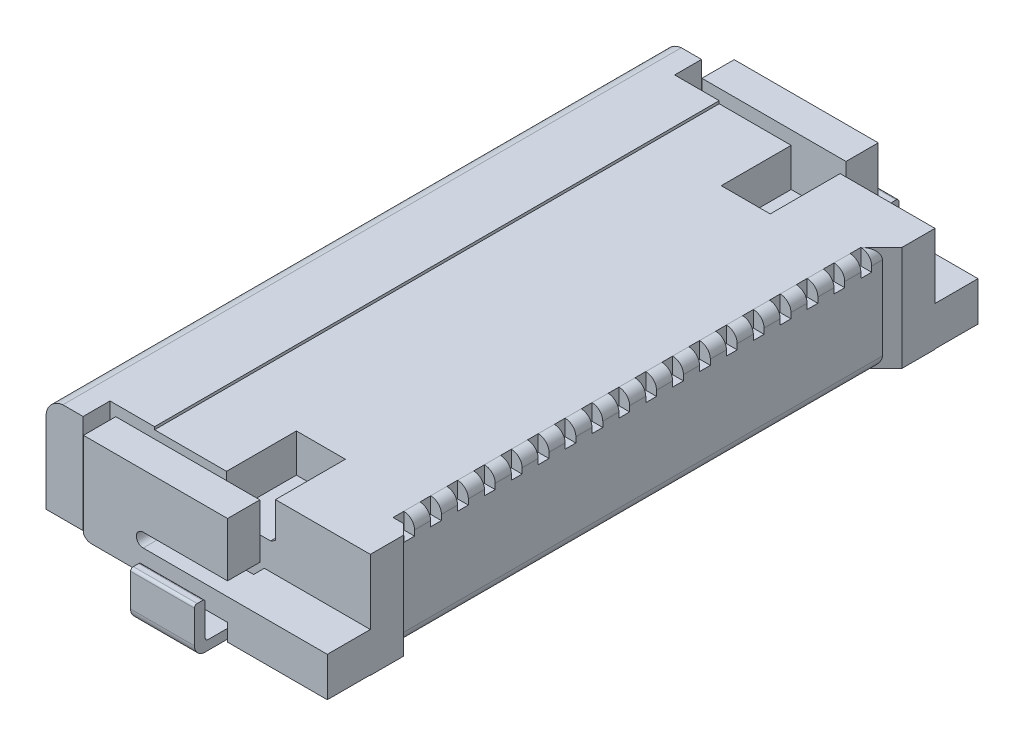
SolidWorks part; units mm, degrees
ref_plane "Front Plane" through (0, 0, 0) normal (0, 0, 1) x (1, 0, 0)
ref_plane "Top Plane" through (0, 0, 0) normal (0, 1, 0) x (1, 0, 0)
ref_plane "Right Plane" through (0, 0, 0) normal (1, 0, 0) x (0, 0, -1)
sketch "Sketch5" plane through (0, 0, 0) normal (0, 0, 1) x (1, 0, 0)
  line L0 (40.6667, 46) -> (203.3333, 46) construction
  line L1 (1.0365, 0.0671) -> (5.5705, 0.0671)
  line L2 (5.5705, 0.0671) -> (5.5705, 2.0592)
  line L3 (5.5705, 2.0592) -> (1.0365, 2.0592)
  line L4 (1.0365, 2.0592) -> (1.0365, 0.0671)
  line L5 (1.0365, 0.9096) -> (0.7294, 0.9096)
  line L6 (0.7294, 0.9096) -> (0.7294, 2.0592)
  line L7 (0.7294, 2.0592) -> (1.0365, 2.0592)
  line L8 (2.4126, 0.8573) -> (2.4126, 0.0671)
  line L9 (2.4126, 0.8573) -> (3.5997, 0.8573)
  line L10 (3.5997, 0.8573) -> (3.5997, 0.0671)
  line L11 (3.5997, 0.7994) -> (5.5705, 0.7994)
  line L12 (2.4126, 0.7994) -> (2.1463, 0.7994)
  line L13 (2.1463, 1.0542) -> (3.7156, 1.0542)
  line L14 (3.7156, 1.0542) -> (3.7156, 2.0592)
  line L15 (2.4126, 0.175) -> (1.0365, 0.175)
  line L16 (3.5997, 0.175) -> (5.5705, 0.175)
  line L17 (2.4126, 0.3858) -> (1.1847, 0.3858)
  line L18 (0.0415, 1.6702) -> (0.0415, 0.2199)
  line L19 (0.0415, 0.2199) -> (0.7294, 0.2199)
  line L20 (0.7294, 0.2199) -> (0.7294, 0.9096)
  line L21 (0.7294, 2.0592) -> (0.3527, 2.0592)
  line L22 (3.8064, 2.0592) -> (3.8064, 1.3482)
  line L23 (3.8064, 1.3482) -> (3.7156, 1.2979)
  line L24 (0.9408, 0.9096) -> (0.9408, 1.2134)
  line L25 (0.9408, 1.2134) -> (1.0365, 1.2134)
  line L26 (3.5997, 0.3858) -> (3.7156, 0.3858)
  line L27 (3.7156, 0.3858) -> (3.7156, 0.175)
  arc A0 (2.1463, 0.7994) -> (2.1463, 1.0542) centre (2.1463, 0.9268) cw
  arc A1 (0.0415, 1.6702) -> (0.3527, 2.0592) centre (0.3916, 1.7091) cw
  spline S0 degree 2 poles (1.1847, 0.3858) (1.082, 0.3886) (1.0365, 0.477) knots 0 0 0 1 1 1
extrude "Boss-Extrude1" add sketch "Sketch5" against normal blind 0.6 contours S0 L17 L8 L12 A0 L13 L14 L3 L4
sketch "Sketch7" plane through (0, 0, 0) normal (0, 0, 1) x (1, 0, 0)
  line L0 (5.5705, 0.0671) -> (5.5705, 2.0592) construction
  line L2 (3.7156, 0.3858) -> (3.7156, 0.175) construction
  line L3 (3.5997, 0.3858) -> (3.7156, 0.3858) construction
  line L4 (3.5997, 0.7994) -> (5.5705, 0.7994) construction
  line L10 (5.5705, 0.175) -> (5.5705, 0.7994)
  line L11 (3.7156, 0.175) -> (3.7156, 0.0671)
  line L12 (3.7156, 0.3858) -> (3.7156, 0.175)
  line L13 (3.5997, 0.3858) -> (3.7156, 0.3858)
  line L14 (3.5997, 0.7994) -> (5.5705, 0.7994)
  line L15 (3.5997, 0.7994) -> (3.5997, 0.3858)
  line L16 (1.0365, 0.0671) -> (5.5705, 0.0671) construction
  line L17 (3.7156, 0.0671) -> (5.5705, 0.0671)
  line L18 (5.5705, 0.0671) -> (5.5705, 0.175)
  line L20 (2.4126, 0.3858) -> (3.5997, 0.3858)
  line L21 (2.4126, 0.7994) -> (3.5997, 0.7994)
  line L24 (2.4126, 0.7994) -> (2.4126, 0.3858)
extrude "Boss-Extrude2" add sketch "Sketch7" against normal blind 0.8 separate body contours L17 L18 L10 L14 L15 L13 L12 L11
sketch "Sketch8" plane through (0, 0, 0) normal (0, 0, 1) x (1, 0, 0)
  line L0 (3.5997, 0.7994) -> (2.4126, 0.7994)
  line L1 (3.5997, 0.3858) -> (2.4126, 0.3858)
  line L2 (3.5997, 0.8573) -> (3.5997, 0.0671) construction
  line L3 (2.4126, 0.8573) -> (2.4126, 0.0671) construction
  line L4 (3.5997, 0.7994) -> (3.5997, 0.3858)
  line L5 (2.4126, 0.7994) -> (2.4126, 0.3858)
extrude "Boss-Extrude3" add sketch "Sketch8" against normal blind 0.6
sketch "Sketch11" plane through (0, 0, 0) normal (0, 1, 0) x (1, 0, 0)
  line L0 (5.5705, 0.8) -> (5.5705, 1.4131)
  line L1 (5.5705, 1.4131) -> (5.3077, 1.5403)
  line L2 (5.3077, 1.5403) -> (5.3077, 9.05)
  line L3 (3.5997, 0) -> (5.5705, 0) construction
  line L4 (5.3077, 9.05) -> (1.7077, 9.05)
  line L5 (1.7077, 9.05) -> (1.7077, 0.8)
  line L6 (1.7077, 0.8) -> (5.5705, 0.8)
  dimension "D1" = 9.05
  dimension "D2" = 3.6
ref_plane "Plane1" through (0, 0.06, 0) normal (0, 1, 0) x (1, 0, 0)
sketch "Sketch13" plane through (0, 0.06, 0) normal (0, 1, 0) x (1, 0, 0)
  line L0 (3.7156, 0) -> (1.0365, 0) construction
  line L2 (5.5705, 0.8) -> (5.5705, 1.4131) construction
  line L6 (5.3077, 6.05) -> (1.6924, 6.05)
  line L7 (5.5705, 1.4131) -> (5.3881, 1.5955)
  line L8 (5.5705, 0.8) -> (5.5705, 1.4131)
  line L9 (1.6924, 6.05) -> (1.6924, 0.8)
  line L10 (5.3881, 1.5955) -> (5.3881, 6.05)
  line L11 (1.6924, 0.8) -> (5.5705, 0.8)
  line L12 (5.3881, 6.05) -> (5.3077, 6.05)
  dimension "D1" = 6.05
extrude "Boss-Extrude5" add sketch "Sketch13" along normal up to surface (1.9992 mm away) up to face at (2.376, 2.0592, -0.3)
sketch "Sketch17" plane through (0, 0, -0.8) normal (0, 0, 1) x (1, 0, 0)
  line L0 (3.8064, 1.3482) -> (3.7156, 1.2979) construction
  line L1 (3.8064, 2.0592) -> (3.8064, 1.3482) construction
  line L2 (3.8064, 1.3482) -> (3.7156, 1.2979)
  line L3 (3.8064, 2.0592) -> (3.8064, 1.3482)
  line L4 (3.7156, 1.2979) -> (2.8963, 1.2979)
  line L5 (2.8963, 1.2979) -> (2.8963, 2.0592)
  line L6 (1.6924, 2.0592) -> (5.5705, 2.0592) construction
  line L7 (2.8963, 2.0592) -> (3.8064, 2.0592)
extrude "Cut-Extrude6" cut sketch "Sketch17" against normal blind 1.3
sketch "Sketch18" plane through (0, 0, -0.8) normal (0, 0, 1) x (1, 0, 0)
  line L0 (0.0415, 1.6702) -> (0.0415, 0.2199)
  line L1 (0.7294, 2.0592) -> (0.7294, 0.9096)
  line L5 (0.0415, 0.2199) -> (0.7294, 0.2199) construction
  line L6 (0.7294, 0.2199) -> (0.7294, 0.9096) construction
  line L9 (0.7294, 2.0592) -> (0.3527, 2.0592) construction
  line L15 (0.0415, 0.2199) -> (0.7294, 0.2199)
  line L16 (0.7294, 0.2199) -> (0.7294, 0.9096)
  line L19 (0.7294, 2.0592) -> (0.3527, 2.0592)
  arc A0 (0.3527, 2.0592) -> (0.0415, 1.6702) centre (0.3916, 1.7091) ccw construction
  arc A1 (0.3527, 2.0592) -> (0.0415, 1.6702) centre (0.3916, 1.7091) ccw
sketch "Sketch19" plane through (1.6924, 0, 0) normal (-1, 0, 0) x (0, 0, 1)
  line L0 (-6.05, 2.0592) -> (-0.8, 2.0592) construction
  line L1 (-6.05, 2.0592) -> (-0.8, 2.0592)
  line L4 (-0.8, 2.0592) -> (-6.05, 2.0592)
  line L5 (-6.05, 2.0592) -> (-6.05, 0.06)
  line L6 (-6.05, 0.06) -> (-0.8, 0.06)
  line L7 (-0.8, 0.06) -> (-0.8, 2.0592)
  line L9 (-6.05, 2.0592) -> (-6.05, 0.06)
  line L10 (-6.05, 0.06) -> (-0.8, 0.06)
  line L11 (-0.8, 0.06) -> (-0.8, 2.0592)
  dimension "D1" = 0
extrude "Boss-Extrude6" add sketch "Sketch19" along normal up to vertex (0.963 mm away) separate body up to point (0.7294, 2.0592, -0.8)
extrude "Boss-Extrude7" add sketch "Sketch18" against normal up to surface (5.25 mm away) up to face at (3.5403, 1.0596, -6.05)
sketch "Sketch20" plane through (0, 0, -0.8) normal (0, 0, 1) x (1, 0, 0)
  line L0 (1.0365, 2.0592) -> (1.0365, 0.0671) construction
  line L1 (0.7294, 0.2199) -> (0.7294, 0.9096) construction
  line L2 (1.0365, 0.9096) -> (0.7294, 0.9096) construction
  line L3 (1.0365, 2.0592) -> (1.0365, 0.0671)
  line L4 (0.7294, 0.2199) -> (0.7294, 0.9096)
  line L5 (1.0365, 0.9096) -> (0.7294, 0.9096)
  line L6 (0.7294, 0.2199) -> (0.7294, 0.06)
  line L7 (0.7294, -0.0203) -> (1.0365, -0.0203)
  line L8 (1.0365, -0.0203) -> (1.0365, 0.0671)
  line L9 (0.7294, 0.06) -> (0.7294, -0.0203)
extrude "Cut-Extrude7" cut sketch "Sketch20" against normal up to surface (5.25 mm away)
sketch "Sketch21" plane through (0, 0, -0.8) normal (0, 0, 1) x (1, 0, 0)
  line L0 (0.7294, 0.2199) -> (0.7294, 0.9096) construction
  line L1 (0.0415, 0.2199) -> (0.7294, 0.2199) construction
  line L2 (0.0415, 1.6702) -> (0.0415, 0.2199) construction
  line L3 (0.7294, 2.0592) -> (0.3527, 2.0592) construction
  line L4 (0.7294, 0.9096) -> (0.7294, 2.0592) construction
  line L5 (0.7294, 0.2199) -> (0.7294, 0.9096)
  line L6 (0.0415, 0.2199) -> (0.7294, 0.2199)
  line L7 (0.0415, 1.6702) -> (0.0415, 0.2199)
  line L8 (0.7294, 2.0592) -> (0.3527, 2.0592)
  line L9 (0.7294, 0.9096) -> (0.7294, 2.0592)
  arc A0 (0.3527, 2.0592) -> (0.0415, 1.6702) centre (0.3916, 1.7091) ccw construction
  arc A1 (0.3527, 2.0592) -> (0.0415, 1.6702) centre (0.3916, 1.7091) ccw
extrude "Boss-Extrude8" add sketch "Sketch21" along normal blind 0.5
mirror "Mirror1" of "Boss-Extrude8", "Cut-Extrude7", "Boss-Extrude7", "Boss-Extrude6", "Cut-Extrude6", "Boss-Extrude5", "Boss-Extrude3", "Boss-Extrude2", "Boss-Extrude1"
sketch "Sketch22" plane through (0, 2.0592, 0) normal (0, 1, 0) x (1, 0, 0)
  line L0 (1.5582, 11.3) -> (1.5582, 0.8)
  line L20 (2.8963, 10) -> (2.8963, 11.3)
  line L21 (2.8963, 11.3) -> (0.7294, 11.3)
  line L22 (0.7294, 11.3) -> (0.7294, 11.8)
  line L23 (0.7294, 11.8) -> (0.3527, 11.8)
  line L24 (0.3527, 11.8) -> (0.3527, 0.3)
  line L25 (0.3527, 0.3) -> (0.7294, 0.3)
  line L26 (0.7294, 0.3) -> (0.7294, 0.8)
  line L27 (0.7294, 0.8) -> (2.8963, 0.8)
  line L28 (2.8963, 0.8) -> (2.8963, 2.1)
  line L29 (2.8963, 2.1) -> (3.8064, 2.1)
  line L30 (3.8064, 2.1) -> (3.8064, 0.8)
  line L31 (3.8064, 0.8) -> (5.5705, 0.8)
  line L32 (5.5705, 0.8) -> (5.5705, 1.4131)
  line L33 (5.5705, 1.4131) -> (5.3881, 1.5955)
  line L34 (5.5705, 1.4131) -> (5.3881, 1.5955)
  line L35 (5.3881, 1.5955) -> (5.3881, 10.5045)
  line L36 (5.5705, 10.6869) -> (5.5705, 11.3)
  line L37 (5.5705, 11.3) -> (3.8064, 11.3)
  line L38 (3.8064, 11.3) -> (3.8064, 10)
  line L39 (3.8064, 10) -> (2.8963, 10)
  line L40 (2.8963, 10) -> (2.8963, 11.3)
  line L41 (2.8963, 11.3) -> (1.5582, 11.3)
  line L43 (5.3881, 1.5955) -> (5.3881, 10.5045)
  line L44 (5.3881, 10.5045) -> (5.5705, 10.6869)
  line L45 (5.3881, 10.5045) -> (5.5705, 10.6869)
  line L46 (0.7294, 0.3) -> (0.7294, 0.8)
  line L47 (1.5582, 0.8) -> (2.8963, 0.8)
  line L48 (2.8963, 0.8) -> (2.8963, 2.1)
  line L49 (2.8963, 2.1) -> (3.8064, 2.1)
  line L50 (3.8064, 2.1) -> (3.8064, 0.8)
  line L51 (3.8064, 0.8) -> (5.5705, 0.8)
  line L52 (5.5705, 0.8) -> (5.5705, 1.4131)
  line L56 (5.5705, 10.6869) -> (5.5705, 11.3)
  line L57 (5.5705, 11.3) -> (3.8064, 11.3)
  line L58 (3.8064, 11.3) -> (3.8064, 10)
  line L59 (3.8064, 10) -> (2.8963, 10)
  dimension "D1" = 0
extrude "Cut-Extrude8" cut sketch "Sketch22" against normal blind 0.05
fillet "Fillet4" radius 0.2 2 edges at (5.3881, 2.0092, -6.05) (5.3881, 0.06, -6.05)
sketch "Sketch26" plane through (0, 0, 0) normal (0, 0, 1) x (1, 0, 0)
  line L1 (3.5997, 0.8573) -> (3.5997, 0.0671) construction
  line L2 (2.4126, 0.8573) -> (2.4126, 0.0671) construction
  line L3 (2.4126, 0.8573) -> (3.5997, 0.8573) construction
  line L4 (2.4126, 0.0671) -> (2.4126, 0)
  line L5 (3.5997, 0.8573) -> (3.5997, 0.0671)
  line L6 (2.4126, 0.8573) -> (2.4126, 0.0671)
  line L7 (2.4126, 0.8573) -> (3.5997, 0.8573)
  line L8 (2.4126, 0) -> (3.5997, 0)
  line L9 (3.5997, 0) -> (3.5997, 0.0671)
  line L10 (2.4126, 0.175) -> (3.5997, 0.175)
extrude "Boss-Extrude9" add sketch "Sketch26" along normal blind 0.5 contours L10 L6 L4 L8 L9 L5
sketch "Sketch27" plane through (0, 0, 0.5) normal (0, 0, 1) x (1, 0, 0)
  line L0 (2.4126, 0.175) -> (3.5997, 0.175) construction
  line L1 (3.5997, 0.8573) -> (3.5997, 0.0671) construction
  line L2 (2.4126, 0.8573) -> (2.4126, 0.0671) construction
  line L3 (2.4126, 0.8573) -> (3.5997, 0.8573) construction
  line L4 (2.4126, 0.175) -> (3.5997, 0.175)
  line L5 (3.5997, 0.8573) -> (3.5997, 0.175)
  line L6 (2.4126, 0.8573) -> (2.4126, 0.175)
  line L7 (2.4126, 0.8573) -> (3.5997, 0.8573)
extrude "Boss-Extrude10" add sketch "Sketch27" against normal blind 0.2
fillet "Fillet6" radius 0.2 1 edges at (3.0062, 0, 0.5)
fillet "Fillet7" radius 0.05 2 edges at (3.0062, 0.8573, 0.5) (3.0062, 0.8573, 0.3)
sketch "Sketch28" plane through (2.4126, 0, 0) normal (-1, 0, 0) x (0, 0, 1)
  line L0 (-0.8, 0.3858) -> (-0.8, 0.0671) construction
  line L1 (-0.8, 0.3233) -> (-0.8, 0.1393)
  line L2 (0, 0.175) -> (-0.5527, 0.175)
  line L3 (0, 0) -> (-0.5527, 0)
  line L4 (0, 0.175) -> (0, 0)
  arc A0 (-0.5527, 0) -> (-0.8, 0.1393) centre (-0.5056, 0.3729) cw
  arc A1 (-0.5527, 0.175) -> (-0.8, 0.3233) centre (-0.4668, 0.5985) cw
extrude "Boss-Extrude11" add sketch "Sketch28" against normal up to surface (1.1871 mm away) up to face at (3.5997, 0.4287, 0.3046)
ref_plane "Plane3" through (0, 0, -6.05) normal (0, 0, 1) x (1, 0, 0)
mirror "Mirror6" about plane through (0, 0, -6.05) normal (0, 0, 1) of "Boss-Extrude11", "Fillet7", "Fillet6", "Boss-Extrude10", "Boss-Extrude9"
fillet "Fillet8" radius 0.05 1 edges at (3.0062, 0.175, 0.3)
fillet "Fillet9" radius 0.05 1 edges at (3.0062, 0.175, -12.4)
sketch "Sketch34" plane through (0, 2.0092, 0) normal (0, 1, 0) x (1, 0, 0)
  line L0 (6.5746, 9.8045) -> (6.5746, 9.6045)
  line L1 (5.1881, 10.3045) -> (6.5746, 10.3045)
  line L2 (5.1881, 10.3045) -> (5.1881, 10.1045)
  line L3 (5.1881, 10.1045) -> (6.5746, 10.1045)
  line L4 (6.5746, 10.3045) -> (6.5746, 10.1045)
  line L5 (5.1881, 9.8045) -> (6.5746, 9.8045)
  line L6 (5.1881, 9.6045) -> (6.5746, 9.6045)
  line L7 (5.1881, 9.8045) -> (5.1881, 9.6045)
  line L8 (6.5746, 9.3045) -> (6.5746, 9.1045)
  line L9 (5.1881, 9.3045) -> (6.5746, 9.3045)
  line L10 (5.1881, 9.1045) -> (6.5746, 9.1045)
  line L11 (5.1881, 9.3045) -> (5.1881, 9.1045)
  line L12 (6.5746, 8.8045) -> (6.5746, 8.6045)
  line L13 (5.1881, 8.8045) -> (6.5746, 8.8045)
  line L14 (5.1881, 8.6045) -> (6.5746, 8.6045)
  line L15 (5.1881, 8.8045) -> (5.1881, 8.6045)
  line L16 (6.5746, 8.3045) -> (6.5746, 8.1045)
  line L17 (5.1881, 8.3045) -> (6.5746, 8.3045)
  line L18 (5.1881, 8.1045) -> (6.5746, 8.1045)
  line L19 (5.1881, 8.3045) -> (5.1881, 8.1045)
  line L20 (6.5746, 7.8045) -> (6.5746, 7.6045)
  line L21 (5.1881, 7.8045) -> (6.5746, 7.8045)
  line L22 (5.1881, 7.6045) -> (6.5746, 7.6045)
  line L23 (5.1881, 7.8045) -> (5.1881, 7.6045)
  line L24 (6.5746, 7.3045) -> (6.5746, 7.1045)
  line L25 (5.1881, 7.3045) -> (6.5746, 7.3045)
  line L26 (5.1881, 7.1045) -> (6.5746, 7.1045)
  line L27 (5.1881, 7.3045) -> (5.1881, 7.1045)
  line L28 (6.5746, 6.8045) -> (6.5746, 6.6045)
  line L29 (5.1881, 6.8045) -> (6.5746, 6.8045)
  line L30 (5.1881, 6.6045) -> (6.5746, 6.6045)
  line L31 (5.1881, 6.8045) -> (5.1881, 6.6045)
  line L32 (6.5746, 6.3045) -> (6.5746, 6.1045)
  line L33 (5.1881, 6.3045) -> (6.5746, 6.3045)
  line L34 (5.1881, 6.1045) -> (6.5746, 6.1045)
  line L35 (5.1881, 6.3045) -> (5.1881, 6.1045)
  line L36 (6.5746, 5.8045) -> (6.5746, 5.6045)
  line L37 (5.1881, 5.8045) -> (6.5746, 5.8045)
  line L38 (5.1881, 5.6045) -> (6.5746, 5.6045)
  line L39 (5.1881, 5.8045) -> (5.1881, 5.6045)
  line L40 (6.5746, 5.3045) -> (6.5746, 5.1045)
  line L41 (5.1881, 5.3045) -> (6.5746, 5.3045)
  line L42 (5.1881, 5.1045) -> (6.5746, 5.1045)
  line L43 (5.1881, 5.3045) -> (5.1881, 5.1045)
  line L44 (6.5746, 4.8045) -> (6.5746, 4.6045)
  line L45 (5.1881, 4.8045) -> (6.5746, 4.8045)
  line L46 (5.1881, 4.6045) -> (6.5746, 4.6045)
  line L47 (5.1881, 4.8045) -> (5.1881, 4.6045)
  line L48 (6.5746, 4.3045) -> (6.5746, 4.1045)
  line L49 (5.1881, 4.3045) -> (6.5746, 4.3045)
  line L50 (5.1881, 4.1045) -> (6.5746, 4.1045)
  line L51 (5.1881, 4.3045) -> (5.1881, 4.1045)
  line L52 (6.5746, 3.8045) -> (6.5746, 3.6045)
  line L53 (5.1881, 3.8045) -> (6.5746, 3.8045)
  line L54 (5.1881, 3.6045) -> (6.5746, 3.6045)
  line L55 (5.1881, 3.8045) -> (5.1881, 3.6045)
  line L56 (6.5746, 3.3045) -> (6.5746, 3.1045)
  line L57 (5.1881, 3.3045) -> (6.5746, 3.3045)
  line L58 (5.1881, 3.1045) -> (6.5746, 3.1045)
  line L59 (5.1881, 3.3045) -> (5.1881, 3.1045)
  line L60 (6.5746, 2.8045) -> (6.5746, 2.6045)
  line L61 (5.1881, 2.8045) -> (6.5746, 2.8045)
  line L62 (5.1881, 2.6045) -> (6.5746, 2.6045)
  line L63 (5.1881, 2.8045) -> (5.1881, 2.6045)
  line L64 (6.5746, 2.3045) -> (6.5746, 2.1045)
  line L65 (5.1881, 2.3045) -> (6.5746, 2.3045)
  line L66 (5.1881, 2.1045) -> (6.5746, 2.1045)
  line L67 (5.1881, 2.3045) -> (5.1881, 2.1045)
  line L68 (6.5746, 1.8045) -> (6.5746, 1.6045)
  line L69 (5.1881, 1.8045) -> (6.5746, 1.8045)
  line L70 (5.1881, 1.6045) -> (6.5746, 1.6045)
  line L71 (5.1881, 1.8045) -> (5.1881, 1.6045)
  dimension "D1" = 0.2
  dimension "D2" = 18
extrude "Cut-Extrude9" cut sketch "Sketch34" against normal blind 0.3
sketch "Sketch35" plane through (0.0415, 0, 0) normal (-1, 0, 0) x (0, 0, 1)
  line L0 (-10.835, 0.2199) -> (-10.835, 0.9096)
  line L2 (-11.8, 0.2199) -> (-0.3, 0.2199) construction
  line L3 (-9.505, 0.9096) -> (-9.505, 1.2296)
  line L4 (-10.835, 0.2199) -> (-1.265, 0.2199)
  line L5 (-9.505, 1.2296) -> (-2.595, 1.2296)
  line L6 (-1.265, 0.2199) -> (-1.265, 0.9096)
  line L7 (-11.3, 0.9096) -> (-0.8, 0.9096) construction
  line L8 (-6.05, 3.2598) -> (-6.05, -1.1519) construction
  line L9 (-10.835, 0.9096) -> (-9.505, 0.9096)
  line L10 (-1.265, 0.9096) -> (-2.595, 0.9096)
  line L11 (-2.595, 0.9096) -> (-2.595, 1.2296)
  point P16 (-6.05, 1.2296)
  dimension "D1" = 4.785
  dimension "D2" = 1.33
  dimension "D3" = 0.32
extrude "Cut-Extrude10" cut sketch "Sketch35" against normal up to surface (0.688 mm away) up to face at (0.7294, 1.312, -6.05)
sketch "Sketch37" plane through (1.0365, 0, 0) normal (-1, 0, 0) x (0, 0, 1)
  line L0 (-11.3, 0.9096) -> (-0.8, 0.9096) construction
  line L1 (-10.385, 0.9096) -> (-10.185, 0.9096)
  line L2 (-10.835, 0.9096) -> (-10.835, 0.2199) construction
  line L3 (-10.385, 0.9096) -> (-10.185, 0.9096)
  line L4 (-10.385, 0.9096) -> (-10.385, 0.3896)
  line L5 (-10.385, 0.3896) -> (-10.185, 0.3896)
  line L6 (-10.185, 0.9096) -> (-10.185, 0.3896)
  line L7 (-9.885, 0.9096) -> (-9.685, 0.9096)
  line L8 (-9.885, 0.9096) -> (-9.885, 0.3896)
  line L9 (-9.685, 0.9096) -> (-9.685, 0.3896)
  line L10 (-9.885, 0.3896) -> (-9.685, 0.3896)
  line L11 (-9.385, 0.9096) -> (-9.185, 0.9096)
  line L12 (-9.385, 0.9096) -> (-9.385, 0.3896)
  line L13 (-9.185, 0.9096) -> (-9.185, 0.3896)
  line L14 (-9.385, 0.3896) -> (-9.185, 0.3896)
  line L15 (-8.885, 0.9096) -> (-8.685, 0.9096)
  line L16 (-8.885, 0.9096) -> (-8.885, 0.3896)
  line L17 (-8.685, 0.9096) -> (-8.685, 0.3896)
  line L18 (-8.885, 0.3896) -> (-8.685, 0.3896)
  line L19 (-8.385, 0.9096) -> (-8.185, 0.9096)
  line L20 (-8.385, 0.9096) -> (-8.385, 0.3896)
  line L21 (-8.185, 0.9096) -> (-8.185, 0.3896)
  line L22 (-8.385, 0.3896) -> (-8.185, 0.3896)
  line L23 (-7.885, 0.9096) -> (-7.685, 0.9096)
  line L24 (-7.885, 0.9096) -> (-7.885, 0.3896)
  line L25 (-7.685, 0.9096) -> (-7.685, 0.3896)
  line L26 (-7.885, 0.3896) -> (-7.685, 0.3896)
  line L27 (-7.385, 0.9096) -> (-7.185, 0.9096)
  line L28 (-7.385, 0.9096) -> (-7.385, 0.3896)
  line L29 (-7.185, 0.9096) -> (-7.185, 0.3896)
  line L30 (-7.385, 0.3896) -> (-7.185, 0.3896)
  line L31 (-6.885, 0.9096) -> (-6.685, 0.9096)
  line L32 (-6.885, 0.9096) -> (-6.885, 0.3896)
  line L33 (-6.685, 0.9096) -> (-6.685, 0.3896)
  line L34 (-6.885, 0.3896) -> (-6.685, 0.3896)
  line L35 (-6.385, 0.9096) -> (-6.185, 0.9096)
  line L36 (-6.385, 0.9096) -> (-6.385, 0.3896)
  line L37 (-6.185, 0.9096) -> (-6.185, 0.3896)
  line L38 (-6.385, 0.3896) -> (-6.185, 0.3896)
  line L39 (-5.885, 0.9096) -> (-5.685, 0.9096)
  line L40 (-5.885, 0.9096) -> (-5.885, 0.3896)
  line L41 (-5.685, 0.9096) -> (-5.685, 0.3896)
  line L42 (-5.885, 0.3896) -> (-5.685, 0.3896)
  line L43 (-5.385, 0.9096) -> (-5.185, 0.9096)
  line L44 (-5.385, 0.9096) -> (-5.385, 0.3896)
  line L45 (-5.185, 0.9096) -> (-5.185, 0.3896)
  line L46 (-5.385, 0.3896) -> (-5.185, 0.3896)
  line L47 (-4.885, 0.9096) -> (-4.685, 0.9096)
  line L48 (-4.885, 0.9096) -> (-4.885, 0.3896)
  line L49 (-4.685, 0.9096) -> (-4.685, 0.3896)
  line L50 (-4.885, 0.3896) -> (-4.685, 0.3896)
  line L51 (-4.385, 0.9096) -> (-4.185, 0.9096)
  line L52 (-4.385, 0.9096) -> (-4.385, 0.3896)
  line L53 (-4.185, 0.9096) -> (-4.185, 0.3896)
  line L54 (-4.385, 0.3896) -> (-4.185, 0.3896)
  line L55 (-3.885, 0.9096) -> (-3.685, 0.9096)
  line L56 (-3.885, 0.9096) -> (-3.885, 0.3896)
  line L57 (-3.685, 0.9096) -> (-3.685, 0.3896)
  line L58 (-3.885, 0.3896) -> (-3.685, 0.3896)
  line L59 (-3.385, 0.9096) -> (-3.185, 0.9096)
  line L60 (-3.385, 0.9096) -> (-3.385, 0.3896)
  line L61 (-3.185, 0.9096) -> (-3.185, 0.3896)
  line L62 (-3.385, 0.3896) -> (-3.185, 0.3896)
  line L63 (-2.885, 0.9096) -> (-2.685, 0.9096)
  line L64 (-2.885, 0.9096) -> (-2.885, 0.3896)
  line L65 (-2.685, 0.9096) -> (-2.685, 0.3896)
  line L66 (-2.885, 0.3896) -> (-2.685, 0.3896)
  line L67 (-2.385, 0.9096) -> (-2.185, 0.9096)
  line L68 (-2.385, 0.9096) -> (-2.385, 0.3896)
  line L69 (-2.185, 0.9096) -> (-2.185, 0.3896)
  line L70 (-2.385, 0.3896) -> (-2.185, 0.3896)
  line L71 (-1.885, 0.9096) -> (-1.685, 0.9096)
  line L72 (-1.885, 0.9096) -> (-1.885, 0.3896)
  line L73 (-1.685, 0.9096) -> (-1.685, 0.3896)
  line L74 (-1.885, 0.3896) -> (-1.685, 0.3896)
  line M7 (-0.8, 0.9096) -> (-11.3, 0.9096)
  dimension "D1" = 0.2
  dimension "D2" = 0.45
  dimension "D3" = 0.52
  dimension "D4" = 18
extrude "Boss-Extrude12" add sketch "Sketch37" along normal blind 0.05 contours L6 L4 L5 M7 | L8 L10 L9 M7 | L12 L14 L13 M7 | L16 L18 L17 M7 | L20 L22 L21 M7 | L24 L26 L25 M7 | L28 L30 L29 M7 | L32 L34 L33 M7 | L36 L38 L37 M7 | L40 L42 L41 M7 | L44 L46 L45 M7 | L48 L50 L49 M7 | L52 L54 L53 M7 | L56 L58 L57 M7 | L60 L62 L61 M7 | L72 L74 L73 M7 | L68 L70 L69 M7 | L64 L66 L65 M7
sketch "Sketch38" plane through (0.9865, 0, 0) normal (-1, 0, 0) x (0, 0, 1)
  line L0 (-10.385, 0.9096) -> (-10.385, 0.3896) construction
  line L1 (-10.385, 0.8205) -> (-10.185, 0.8205)
  line L2 (-10.385, 0.8205) -> (-10.385, 0.6496)
  line L3 (-10.385, 0.6496) -> (-10.185, 0.6496)
  line L4 (-10.185, 0.8205) -> (-10.185, 0.6496)
  line L5 (-10.185, 0.9096) -> (-10.185, 0.3896) construction
extrude "Boss-Extrude13" add sketch "Sketch38" along normal blind 0.01
pattern_linear "LPattern2" count 18 spacing 0.5 along (0, 0, 1) of "Boss-Extrude13"
